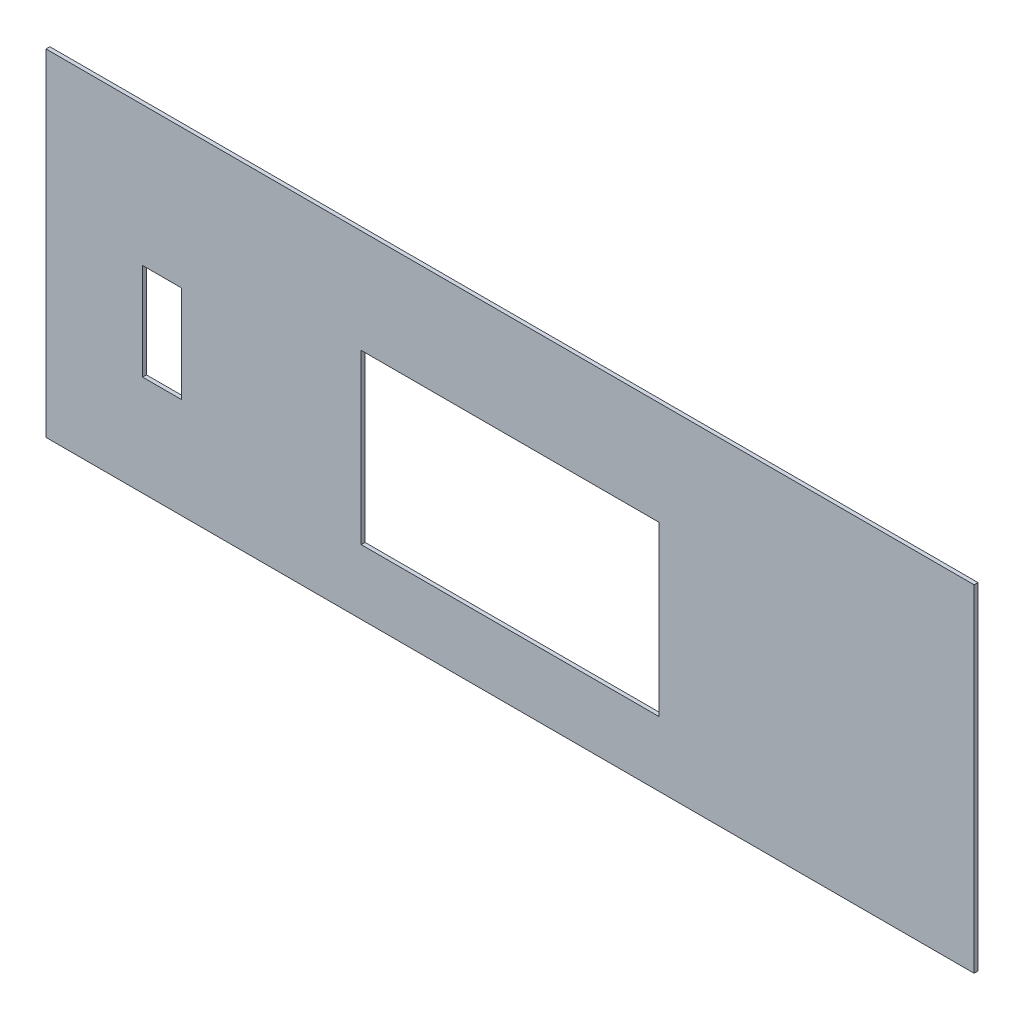
SolidWorks part; units mm, degrees
material "AISI 316 Stainless Steel Sheet (SS)"
ref_plane "Front" through (0, 0, 0) normal (0, 0, 1) x (1, 0, 0)
ref_plane "Top" through (0, 0, 0) normal (0, 1, 0) x (1, 0, 0)
ref_plane "Right" through (0, 0, 0) normal (1, 0, 0) x (0, 0, -1)
sketch "Sketch1" plane through (0, 0, 0) normal (0, 0, 1) x (1, 0, 0)
  line L1 (-240, -87) -> (240, -87)
  line L2 (-240, -87) -> (-240, 87)
  line L3 (-240, 87) -> (240, 87)
  line L4 (240, -87) -> (240, 87)
  line L5 (-240, -87) -> (240, 87) construction
  line L6 (-240, 87) -> (240, -87) construction
  line L7 (-77, 33.5) -> (77, 33.5)
  line L8 (-77, 33.5) -> (-77, -53.5)
  line L9 (-77, -53.5) -> (77, -53.5)
  line L10 (77, 33.5) -> (77, -53.5)
  line L11 (-77, 33.5) -> (77, -53.5) construction
  line L12 (-77, -53.5) -> (77, 33.5) construction
  line L13 (-190, -35) -> (-170, -35)
  line L14 (-190, -35) -> (-190, 15)
  line L15 (-190, 15) -> (-170, 15)
  line L16 (-170, -35) -> (-170, 15)
  point P0 (0, 0)
  point P6 (0, -10)
  point P11 (116.5375, -5.5213)
  point P16 (-180, -35)
  point P17 (-190, -10)
  dimension "D1" = 480
  dimension "D2" = 174
  dimension "D3" = 154
  dimension "D4" = 87
  dimension "D5" = 10
  dimension "D6" = 0
  dimension "D7" = 20
  dimension "D8" = 50
  dimension "D9" = 180
extrude "Boss-Extrude1" add sketch "Sketch1" against normal blind 2
sketch "Sketch2" plane through (0, 0, -2) normal (0, 0, -1) x (-1, 0, 0)
  line L0 (-69, 758.1979) -> (-69, 565.6979) construction
  line L1 (-9, 80) -> (-129, 80)
  line L2 (-9, 80) -> (-9, 240)
  line L3 (-9, 240) -> (-129, 240)
  line L4 (-129, 80) -> (-129, 240)
  line L5 (-9, 80) -> (-129, 240) construction
  line L6 (-9, 240) -> (-129, 80) construction
  point P0 (-69, 160)
  dimension "D1" = 160
  dimension "D2" = 120
  dimension "D3" = 160
surface "door location" [suppressed] sketch "Sketch2" parameters "D1"=10
split "Split1" [suppressed] bodies to split 101
